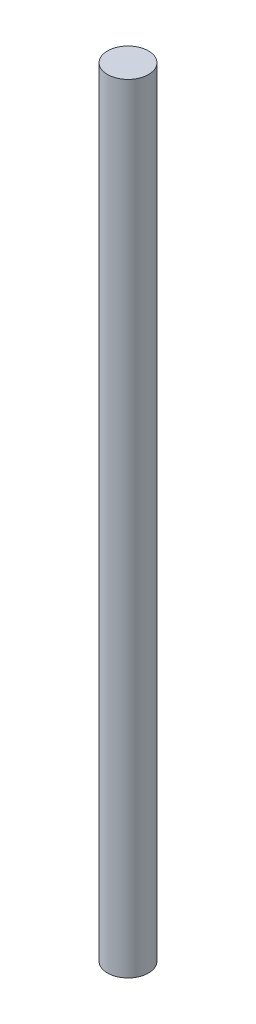
SolidWorks part; units mm, degrees
ref_plane "Front" through (0, 0, 0) normal (0, 0, 1) x (1, 0, 0)
ref_plane "Top" through (0, 0, 0) normal (0, 1, 0) x (1, 0, 0)
ref_plane "Right" through (0, 0, 0) normal (1, 0, 0) x (0, 0, -1)
sketch "Sketch1" plane through (0, 0, 0) normal (0, 1, 0) x (1, 0, 0)
  circle A0 centre (-41.1648, -11.4406) radius 1.5875
extrude "Boss-Extrude1" add sketch "Sketch1" along normal blind 60.325
